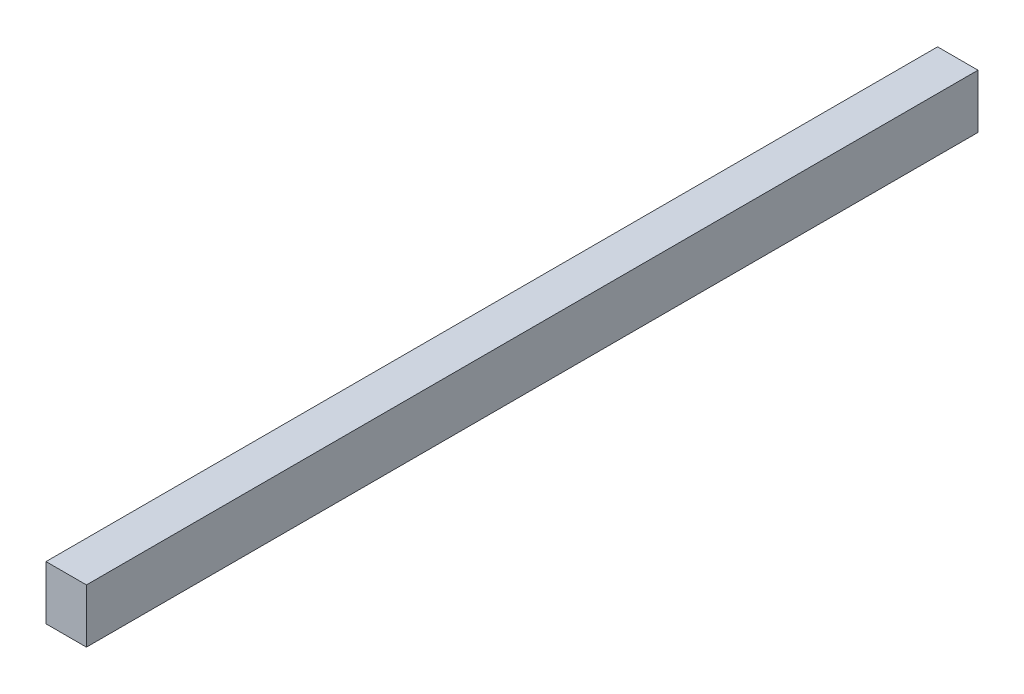
SolidWorks part; units mm, degrees
material "Low Carbon Steel"
ref_plane "Front Plane" through (0, 0, 0) normal (0, 0, 1) x (1, 0, 0)
ref_plane "Top Plane" through (0, 0, 0) normal (0, 1, 0) x (1, 0, 0)
ref_plane "Right Plane" through (0, 0, 0) normal (1, 0, 0) x (0, 0, -1)
sketch "Sketch1" plane through (0, 0, 0) normal (0, 0, 1) x (1, 0, 0)
  line L1 (0, 0) -> (76.2, 0)
  line L2 (0, 0) -> (0, 101.6)
  line L3 (0, 101.6) -> (76.2, 101.6)
  line L4 (76.2, 0) -> (76.2, 101.6)
  dimension "D1" = 76.2
  dimension "D2" = 101.6
extrude "Boss-Extrude1" add sketch "Sketch1" along normal blind 1680
other "Freeze***"
